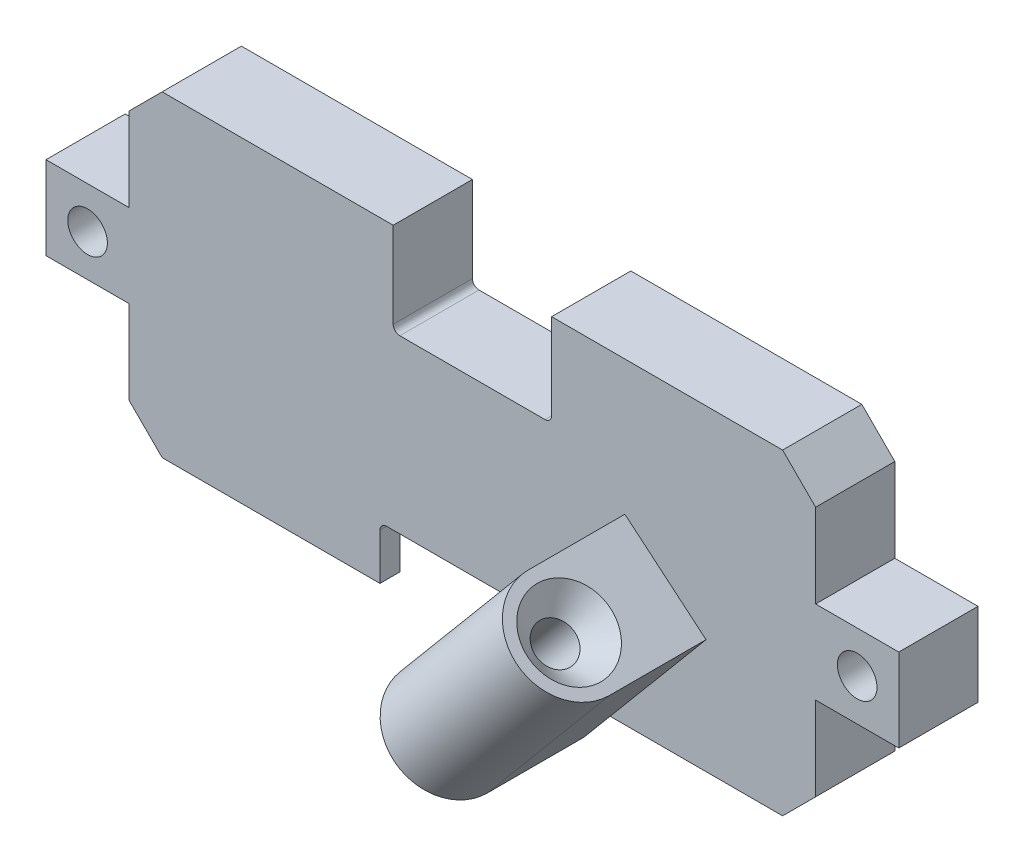
SolidWorks part; units mm, degrees
ref_plane "Front Plane" through (0, 0, 0) normal (0, 0, 1) x (1, 0, 0)
ref_plane "Top Plane" through (0, 0, 0) normal (0, 1, 0) x (1, 0, 0)
ref_plane "Right Plane" through (0, 0, 0) normal (1, 0, 0) x (0, 0, -1)
sketch "Sketch1" plane through (0, 0, 0) normal (0, 0, 1) x (1, 0, 0)
  line L16 (-23.5, -12) -> (-7, -12)
  line L17 (-7, -12) -> (-7, -8.5)
  line L18 (-6.5, -8) -> (6.5, -8)
  line L19 (7, -8.5) -> (7, -12)
  line L20 (7, -12) -> (23.5, -12)
  line L21 (23.5, -12) -> (26, -9.5)
  line L22 (26, -9.5) -> (26, -3.15)
  line L23 (26, 9.5) -> (23.5, 12)
  line L24 (23.5, 12) -> (6, 12)
  line L25 (6, 12) -> (6, 5.5)
  line L26 (5.5, 5) -> (-5.5, 5)
  line L27 (-6, 5.5) -> (-6, 12)
  line L28 (-6, 12) -> (-23.5, 12)
  line L29 (-23.5, 12) -> (-26, 9.5)
  line L30 (-26, 9.5) -> (-26, 3.15)
  line L31 (-26, -9.5) -> (-23.5, -12)
  line L32 (-23.5, -12) -> (-7, -12)
  line L33 (-7, -12) -> (-7, -8.5)
  line L34 (-6.5, -8) -> (6.5, -8)
  line L35 (7, -8.5) -> (7, -12)
  line L36 (7, -12) -> (23.5, -12)
  line L37 (23.5, -12) -> (26, -9.5)
  line L38 (26, -9.5) -> (26, -3.15)
  line L39 (26, 9.5) -> (23.5, 12)
  line L40 (23.5, 12) -> (6, 12)
  line L41 (6, 12) -> (6, 5.5)
  line L42 (5.5, 5) -> (-5.5, 5)
  line L43 (-6, 5.5) -> (-6, 12)
  line L44 (-6, 12) -> (-23.5, 12)
  line L45 (-23.5, 12) -> (-26, 9.5)
  line L46 (-26, 9.5) -> (-26, 3.15)
  line L47 (-26, -9.5) -> (-23.5, -12)
  line L224 (26, -3.15) -> (32.3, -3.15)
  line L225 (26, -3.15) -> (32.3, -3.15)
  line L226 (32.3, -3.15) -> (32.3, 3.15)
  line L227 (32.3, -3.15) -> (32.3, 3.15)
  line L228 (32.3, 3.15) -> (26, 3.15)
  line L229 (32.3, 3.15) -> (26, 3.15)
  line L230 (26, 3.15) -> (26, 9.5)
  line L231 (26, 3.15) -> (26, 9.5)
  line L232 (-26, 3.15) -> (-32.3, 3.15)
  line L233 (-26, 3.15) -> (-32.3, 3.15)
  line L234 (-32.3, 3.15) -> (-32.3, -3.15)
  line L235 (-32.3, 3.15) -> (-32.3, -3.15)
  line L236 (-32.3, -3.15) -> (-26, -3.15)
  line L237 (-32.3, -3.15) -> (-26, -3.15)
  line L238 (-26, -3.15) -> (-26, -9.5)
  line L239 (-26, -3.15) -> (-26, -9.5)
  arc A4 (-6.5, -8) -> (-7, -8.5) centre (-6.5, -8.5) ccw
  arc A5 (7, -8.5) -> (6.5, -8) centre (6.5, -8.5) ccw
  arc A6 (5.5, 5) -> (6, 5.5) centre (5.5, 5.5) ccw
  arc A7 (-6, 5.5) -> (-5.5, 5) centre (-5.5, 5.5) ccw
  arc A8 (-6.5, -8) -> (-7, -8.5) centre (-6.5, -8.5) ccw
  arc A9 (7, -8.5) -> (6.5, -8) centre (6.5, -8.5) ccw
  arc A10 (5.5, 5) -> (6, 5.5) centre (5.5, 5.5) ccw
  arc A11 (-6, 5.5) -> (-5.5, 5) centre (-5.5, 5.5) ccw
  dimension "D1" = 0
extrude "Boss-Extrude1" add sketch "Sketch1" along normal blind 6 from offset 5
chamfer "Chamfer1" distance 4.5 5 edges at (-7, -10.25, 5) (7, -10.25, 5) (-6.8536, -8.1464, 5) (6.8536, -8.1464, 5) (0, -8, 5)
sketch "Sketch2" plane through (26, 0, 0) normal (1, 0, 0) x (0, 0, -1)
  line L0 (-11, -9.5) -> (-11, -3.15) construction
  line L1 (-11, 3.15) -> (-5, 3.15)
  line L2 (-11, 3.15) -> (-11, -3.15)
  line L3 (-11, -3.15) -> (-5, -3.15)
  line L4 (-5, 3.15) -> (-5, -3.15)
  line L5 (-5, -9.5) -> (-5, -3.15) construction
  point P8 (-5, 0)
  dimension "D1" = 6.3
extrude "Boss-Extrude2" add sketch "Sketch2" along normal blind 6.3
mirror "Mirror1" about plane through (0, 0, 0) normal (1, 0, 0) of "Boss-Extrude2"
sketch "Sketch3" plane through (0, 0, 11) normal (0, 0, 1) x (1, 0, 0)
  line L0 (11.5514, 1.8168) -> (2.2919, -9.2183)
  line L1 (2.2919, -9.2183) -> (8.4391, -14.3764)
  line L2 (8.4391, -14.3764) -> (17.6986, -3.3413)
  line L4 (26, 9.5) -> (23.5, 12)
  line L5 (11.5514, 1.8168) -> (17.6986, -3.3413)
  line L6 (7, -12) -> (23.5, -12) construction
  dimension "D1" = 30
  dimension "D2" = 50
extrude "Boss-Extrude3" add sketch "Sketch3" along normal blind 7.3 contours L1 L2 L5 L0
sketch "Sketch4" plane through (5.6674, 6.7541, 0) normal (0.6428, 0.766, 0) x (0.766, -0.6428, 0)
  line L0 (7.6811, -18.3) -> (15.7056, -18.3) construction
  line L1 (15.7056, -18.3) -> (7.6811, -18.3)
  arc A0 (15.7056, -18.3) -> (7.6811, -18.3) centre (11.6933, -18.3) cw
extrude "Boss-Extrude4" add sketch "Sketch4" against normal up to vertex
hole_wizard "CSK for M3 SFHCS1" positions "Sketch5" profile "Sketch6" countersink size "M3" standard "ANSI Metric" end condition through all
sketch "Sketch5" plane through (5.6674, 6.7541, 0) normal (0.6428, 0.766, 0) x (0.766, -0.6428, 0)
  point P0 (11.6933, -18.3)
sketch "Sketch6" plane through (14.625, -0.7622, 18.3) normal (0, 0, 1) x (-0.766, 0.6428, 0)
  line L0 (0, 0) -> (0, 40.5919)
  line L1 (0, 40.5919) -> (1.5, 40.5919)
  line L2 (1.5, 40.5919) -> (1.5, 1.65)
  line L3 (1.5, 1.65) -> (3.15, 0)
  line L5 (3.15, 0) -> (0, 0)
  line L6 (-1.5, 1.65) -> (-3.15, 0) construction
  line L11 (0, -6.35) -> (0, 107.95) construction
  dimension "Thru Hole Dia." = 3
  dimension "Thru Hole Depth" = 40.5919
  dimension "Near C'Sink Dia." = 6.3
  dimension "Near C'Sink Angle" = 90
hole_wizard "CSK for M3 SFHCS2" positions "Sketch7" profile "Sketch8" countersink size "M3" standard "ANSI Metric" end condition through all
sketch "Sketch7" plane through (-1490.3777, -7.8258, -12) normal (0, 0, -1) x (-0.766, 0.6428, 0)
  line L0 (-1161.4085, 984.7533) -> (-1111.922, 943.2292)
  line L6 (-1156.9707, 985.1415) -> (-1161.0202, 980.3154)
  line L11 (-1112.3103, 947.667) -> (-1116.3598, 942.8409)
  point P2 (-1114.3351, 945.254)
  point P48 (-1158.9954, 982.7285)
sketch "Sketch8" plane through (-29.15, 0, -12) normal (1, 0, 0) x (0, 1, 0)
  line L0 (0, 0) -> (0, 34.3123)
  line L1 (0, 34.3123) -> (1.5, 34.3123)
  line L2 (1.5, 34.3123) -> (1.5, 1.65)
  line L3 (1.5, 1.65) -> (3.15, 0)
  line L4 (3.15, 0) -> (0, 0)
  line L5 (-1.5, 1.65) -> (-3.15, 0) construction
  line L6 (0, -6.35) -> (0, 107.95) construction
  dimension "Thru Hole Dia." = 3
  dimension "Thru Hole Depth" = 34.3123
  dimension "Near C'Sink Dia." = 6.3
  dimension "Near C'Sink Angle" = 90
